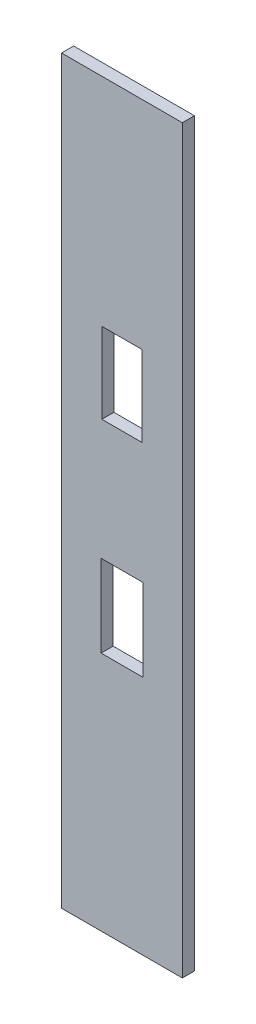
SolidWorks part; units mm, degrees
ref_plane "Alzado" through (0, 0, 0) normal (0, 0, 1) x (1, 0, 0)
ref_plane "Planta" through (0, 0, 0) normal (0, 1, 0) x (1, 0, 0)
ref_plane "Vista lateral" through (0, 0, 0) normal (1, 0, 0) x (0, 0, -1)
sketch "Croquis1" plane through (0, 0, 0) normal (0, 0, 1) x (1, 0, 0)
  line L1 (75, -460) -> (-75, -460)
  line L2 (75, -460) -> (75, 460)
  line L3 (75, 460) -> (-75, 460)
  line L4 (-75, -460) -> (-75, 460)
  line L5 (75, -460) -> (-75, 460) construction
  line L6 (75, 460) -> (-75, -460) construction
  point P0 (0, 0)
  dimension "D1" = 920
  dimension "D2" = 150
extrude "Saliente-Extruir1" add sketch "Croquis1" along normal blind 15
sketch "Croquis3" plane through (0, 0, 0) normal (0, 0, -1) x (-1, 0, 0)
  line L0 (0, -460) -> (0, 460) construction
  line L1 (75, -460) -> (-75, -460) construction
  line L2 (-75, 460) -> (75, 460) construction
  line L4 (26, -161) -> (-26, -161)
  line L5 (26, -161) -> (26, -59)
  line L6 (26, -59) -> (-26, -59)
  line L7 (-26, -161) -> (-26, -59)
  line L8 (26, -161) -> (-26, -59) construction
  line L9 (26, -59) -> (-26, -161) construction
  point P6 (0, -110)
  dimension "D1" = 52
  dimension "D2" = 102
  dimension "D3" = 350
extrude "Cortar-Extruir1" cut sketch "Croquis3" against normal mid plane 400
sketch "Croquis5" plane through (0, 0, 15) normal (0, 0, 1) x (1, 0, 0)
  line L0 (0, -59) -> (0, 141) construction
  line L1 (26, -59) -> (-26, -59) construction
  line L3 (-50, 169) -> (50, 169)
  line L4 (-50, 169) -> (-50, 113)
  line L5 (-50, 113) -> (50, 113)
  line L6 (50, 169) -> (50, 113)
  line L7 (-50, 169) -> (50, 113) construction
  line L8 (-50, 113) -> (50, 169) construction
  dimension "D1" = 100
  dimension "D2" = 56
  dimension "D3" = 200
sketch "Croquis7" plane through (0, 0, 0) normal (0, 0, -1) x (-1, 0, 0)
  line L1 (-25, 191) -> (25, 191)
  line L2 (-25, 191) -> (-25, 91)
  line L3 (-25, 91) -> (25, 91)
  line L4 (25, 191) -> (25, 91)
  line L5 (-25, 191) -> (25, 91) construction
  line L6 (-25, 91) -> (25, 191) construction
  point P0 (0, 141)
  dimension "D1" = 100
  dimension "D2" = 50
extrude "Cortar-Extruir2" cut sketch "Croquis7" against normal through all
